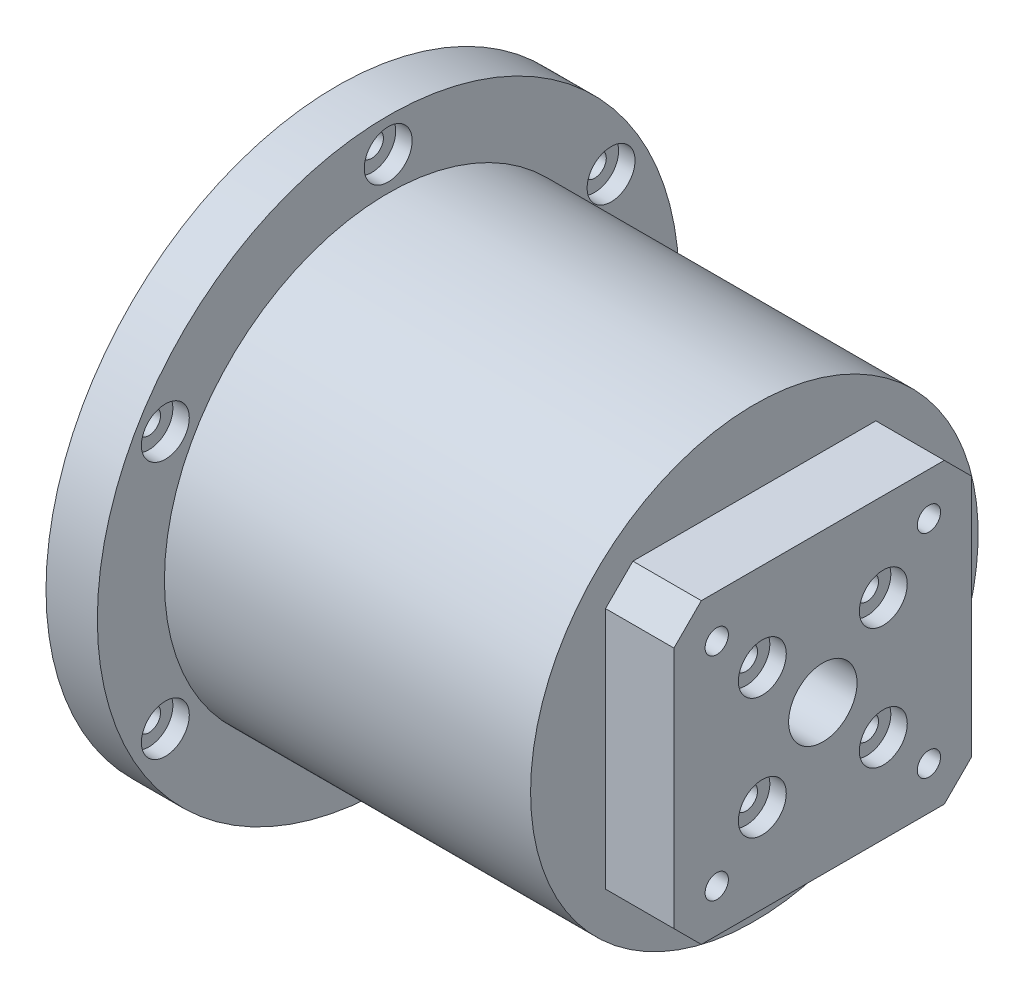
SolidWorks part; units mm, degrees
material "ABS"
ref_plane "Front" through (0, 0, 0) normal (0, 0, 1) x (1, 0, 0)
ref_plane "Top" through (0, 0, 0) normal (0, 1, 0) x (1, 0, 0)
ref_plane "Right" through (0, 0, 0) normal (1, 0, 0) x (0, 0, -1)
sketch "Croquis1" plane through (0, 0, 0) normal (1, 0, 0) x (0, 0, -1)
  line L0 (-21.75, -17.75) -> (-21.75, 17.75)
  line L1 (-21.75, -21.75) -> (21.75, -21.75) construction
  line L2 (-21.75, -21.75) -> (-21.75, 21.75) construction
  line L3 (-21.75, 21.75) -> (21.75, 21.75) construction
  line L4 (21.75, -21.75) -> (21.75, 21.75) construction
  line L5 (-21.75, -21.75) -> (21.75, 21.75) construction
  line L6 (-21.75, 21.75) -> (21.75, -21.75) construction
  line L7 (-21.75, 17.75) -> (-17.75, 21.75)
  line L8 (-17.75, 21.75) -> (17.75, 21.75)
  line L9 (17.75, 21.75) -> (21.75, 17.75)
  line L10 (21.75, 17.75) -> (21.75, -17.75)
  line L11 (21.75, -17.75) -> (17.75, -21.75)
  line L12 (17.75, -21.75) -> (-17.75, -21.75)
  line L13 (-17.75, -21.75) -> (-21.75, -17.75)
  circle A0 centre (0, 0) radius 5
  point P0 (0, 0)
  dimension "D4" = 10
  dimension "D1" = 43.5
  dimension "D2" = 4
  dimension "D3" = 4
extrude "Saliente-Extruir1" add sketch "Croquis1" along normal blind 10
sketch "Croquis2" plane through (0, 0, 0) normal (-1, 0, 0) x (0, 0, 1)
  circle A0 centre (0, 0) radius 32.7
  dimension "D1" = 65.4
extrude "Saliente-Extruir2" add sketch "Croquis2" along normal blind 53.5
sketch "Croquis3" plane through (-53.5, 0, 0) normal (-1, 0, 0) x (0, 0, 1)
  circle A0 centre (0, 0) radius 21.5
  dimension "D1" = 43
extrude "Cortar-Extruir2" cut sketch "Croquis3" against normal offset from surface (55 mm away) 8.5 contours A0 up to face at (10, 0, 0)
hole_wizard "Refrentado para tornillo con cabeza troncocónica de M31" positions "Croquis4" profile "Croquis6" counterbore size "M3" standard "Ansi Metric" end condition up to next
sketch "Croquis4" plane through (10, 0, 0) normal (1, 0, 0) x (0, 0, -1)
  line L0 (0, 0) -> (-8.8388, 8.8388) construction
  line L3 (0, 50) -> (0, -50) construction
  point P0 (-8.8388, 8.8388)
  point P16 (8.8388, 8.8388)
  point P17 (8.8388, -8.8388)
  point P18 (-8.8388, -8.8388)
  dimension "D1" = 45
  dimension "D2" = 12.5
  dimension "D3" = 4
sketch "Croquis6" plane through (10, 8.8388, 8.8388) normal (0, 1, 0) x (0, 0, -1)
  line L0 (0, 0) -> (0, 8.5)
  line L1 (0, 8.5) -> (1.7, 8.5)
  line L3 (1.7, 8.5) -> (1.7, 2.4)
  line L4 (1.7, 2.4) -> (3.5, 2.4)
  line L5 (3.5, 2.4) -> (3.5, 0)
  line L7 (3.5, 0) -> (0, 0)
  line L11 (0, -6.35) -> (0, 107.95) construction
  dimension "Diámetro de taladro hasta el siguiente" = 3.4
  dimension "Profundidad de taladro hasta el siguiente" = 8.5
  dimension "Diámetro de refrentado" = 7
  dimension "Profundidad de refrentado" = 2.4
hole_wizard "Taladro de margen para M31" positions "Croquis7" profile "Croquis9" hole size "M3" standard "Ansi Metric"
sketch "Croquis7" plane through (10, 0, 0) normal (1, 0, 0) x (0, 0, -1)
  line L0 (0, 0) -> (15.5, 15.5) construction
  line L3 (0, 50) -> (0, -50) construction
  line L4 (50, 0) -> (-50, 0) construction
  point P0 (15.5, 15.5)
  point P17 (15.5, -15.5)
  point P18 (-15.5, -15.5)
  point P19 (-15.5, 15.5)
  dimension "D1" = 45
  dimension "D2" = 15.5
  dimension "D3" = 4
sketch "Croquis9" plane through (10, 15.5, -15.5) normal (0, 1, 0) x (0, 0, -1)
  line L0 (0, 0) -> (0, 17.0215)
  line L1 (0, 17.0215) -> (1.7, 16)
  line L2 (1.7, 16) -> (1.7, 0)
  line L5 (1.7, 0) -> (0, 0)
  line L10 (0, 17.0215) -> (-1.7, 16) construction
  line L11 (0, -6.35) -> (0, 107.95) construction
  dimension "Diámetro de taladro" = 3.4
  dimension "Profundidad de taladro" = 16
  dimension "Ángulo de perforador" = 118
sketch "Croquis10" plane through (1.5, 0, 0) normal (-1, 0, 0) x (0, 0, 1)
  line L0 (0, 0) -> (-15.5, 15.5) construction
  line L1 (-13.2514, 13.2514) -> (-12.4284, 16.323)
  line L2 (-12.4284, 16.323) -> (-14.677, 18.5716)
  line L3 (-14.677, 18.5716) -> (-17.7486, 17.7486)
  line L4 (-17.7486, 17.7486) -> (-18.5716, 14.677)
  line L5 (-18.5716, 14.677) -> (-16.323, 12.4284)
  line L6 (-16.323, 12.4284) -> (-13.2514, 13.2514)
  line L7 (18.5716, 14.677) -> (17.7486, 17.7486)
  line L8 (16.323, 12.4284) -> (18.5716, 14.677)
  line L9 (13.2514, 13.2514) -> (16.323, 12.4284)
  line L10 (12.4284, 16.323) -> (13.2514, 13.2514)
  line L11 (14.677, 18.5716) -> (12.4284, 16.323)
  line L12 (17.7486, 17.7486) -> (14.677, 18.5716)
  line L13 (14.677, -18.5716) -> (17.7486, -17.7486)
  line L14 (12.4284, -16.323) -> (14.677, -18.5716)
  line L15 (13.2514, -13.2514) -> (12.4284, -16.323)
  line L16 (16.323, -12.4284) -> (13.2514, -13.2514)
  line L17 (18.5716, -14.677) -> (16.323, -12.4284)
  line L18 (17.7486, -17.7486) -> (18.5716, -14.677)
  line L19 (-18.5716, -14.677) -> (-17.7486, -17.7486)
  line L20 (-16.323, -12.4284) -> (-18.5716, -14.677)
  line L21 (-13.2514, -13.2514) -> (-16.323, -12.4284)
  line L22 (-12.4284, -16.323) -> (-13.2514, -13.2514)
  line L23 (-14.677, -18.5716) -> (-12.4284, -16.323)
  line L24 (-17.7486, -17.7486) -> (-14.677, -18.5716)
  circle A0 centre (-15.5, 15.5) radius 2.754 construction
  dimension "D1" = 3.18
  dimension "D2" = 4
extrude "Cortar-Extruir3" cut sketch "Croquis10" along normal blind 5
sketch "Croquis11" plane through (-53.5, 0, 0) normal (-1, 0, 0) x (0, 0, 1)
  line L0 (-21.5, -17.75) -> (-21.5, 17.75)
  line L1 (-21.5, -21.5) -> (21.5, -21.5) construction
  line L2 (-21.5, -21.5) -> (-21.5, 21.5) construction
  line L3 (-21.5, 21.5) -> (21.5, 21.5) construction
  line L4 (21.5, -21.5) -> (21.5, 21.5) construction
  line L5 (-21.5, -21.5) -> (21.5, 21.5) construction
  line L6 (-21.5, 21.5) -> (21.5, -21.5) construction
  line L7 (-21.5, 17.75) -> (-17.75, 21.5)
  line L8 (-17.75, 21.5) -> (17.75, 21.5)
  line L9 (17.75, 21.5) -> (21.5, 17.75)
  line L10 (21.5, 17.75) -> (21.5, -17.75)
  line L11 (21.5, -17.75) -> (17.75, -21.5)
  line L12 (17.75, -21.5) -> (-17.75, -21.5)
  line L13 (-17.75, -21.5) -> (-21.5, -17.75)
  circle A0 centre (0, 0) radius 42.5
  point P15 (0, 0)
  dimension "D1" = 85
  dimension "D2" = 43
  dimension "D3" = 3.75
  dimension "D4" = 3.75
extrude "Saliente-Extruir3" add sketch "Croquis11" along normal blind 7.5
hole_wizard "Taladro de margen para M32" positions "Croquis12" profile "Croquis13" hole size "M3" standard "Ansi Metric"
sketch "Croquis12" plane through (-53.5, 0, 0) normal (-1, 0, 0) x (0, 0, 1)
  line L0 (0, 0) -> (-17.075, 17.075) construction
  line L3 (0, -50) -> (0, 50) construction
  line L4 (50, 0) -> (-50, 0) construction
  point P0 (-17.075, 17.075)
  point P18 (17.075, 17.075)
  point P19 (17.075, -17.075)
  point P20 (-17.075, -17.075)
  dimension "D1" = 45
  dimension "D2" = 17.075
  dimension "D3" = 4
sketch "Croquis13" plane through (-53.5, 17.075, -17.075) normal (0, 1, 0) x (0, 0, 1)
  line L0 (0, 0) -> (0, 17.0215)
  line L1 (0, 17.0215) -> (1.7, 16)
  line L2 (1.7, 16) -> (1.7, 0)
  line L5 (1.7, 0) -> (0, 0)
  line L10 (0, 17.0215) -> (-1.7, 16) construction
  line L11 (0, -6.35) -> (0, 107.95) construction
  dimension "Diámetro de taladro" = 3.4
  dimension "Profundidad de taladro" = 16
  dimension "Ángulo de perforador" = 118
hole_wizard "Refrentado para tornillo con cabeza troncocónica de M32" positions "Croquis14" profile "Croquis16" counterbore size "M3" standard "Ansi Metric" end condition up to next
sketch "Croquis14" plane through (-53.5, 0, 0) normal (1, 0, 0) x (0, 0, -1)
  line L0 (0, 50) -> (0, -50) construction
  line L1 (0, 42.5) -> (0, 32.7) construction
  circle A0 centre (0, 0) radius 42.5 construction
  circle A1 centre (0, 0) radius 32.7 construction
  point P0 (0, 37.6)
  point P15 (0, 37.6)
  point P20 (32.5626, 18.8)
  point P21 (32.5626, -18.8)
  point P22 (0, -37.6)
  point P23 (-32.5626, -18.8)
  point P24 (-32.5626, 18.8)
  dimension "D1" = 6
sketch "Croquis16" plane through (-53.5, 37.6, 0) normal (0, 1, 0) x (0, 0, -1)
  line L0 (0, 0) -> (0, 7.5)
  line L1 (0, 7.5) -> (1.7, 7.5)
  line L3 (1.7, 7.5) -> (1.7, 2.4)
  line L4 (1.7, 2.4) -> (3.5, 2.4)
  line L5 (3.5, 2.4) -> (3.5, 0)
  line L7 (3.5, 0) -> (0, 0)
  line L11 (0, -6.35) -> (0, 107.95) construction
  dimension "Diámetro de taladro hasta el siguiente" = 3.4
  dimension "Profundidad de taladro hasta el siguiente" = 7.5
  dimension "Diámetro de refrentado" = 7
  dimension "Profundidad de refrentado" = 2.4
